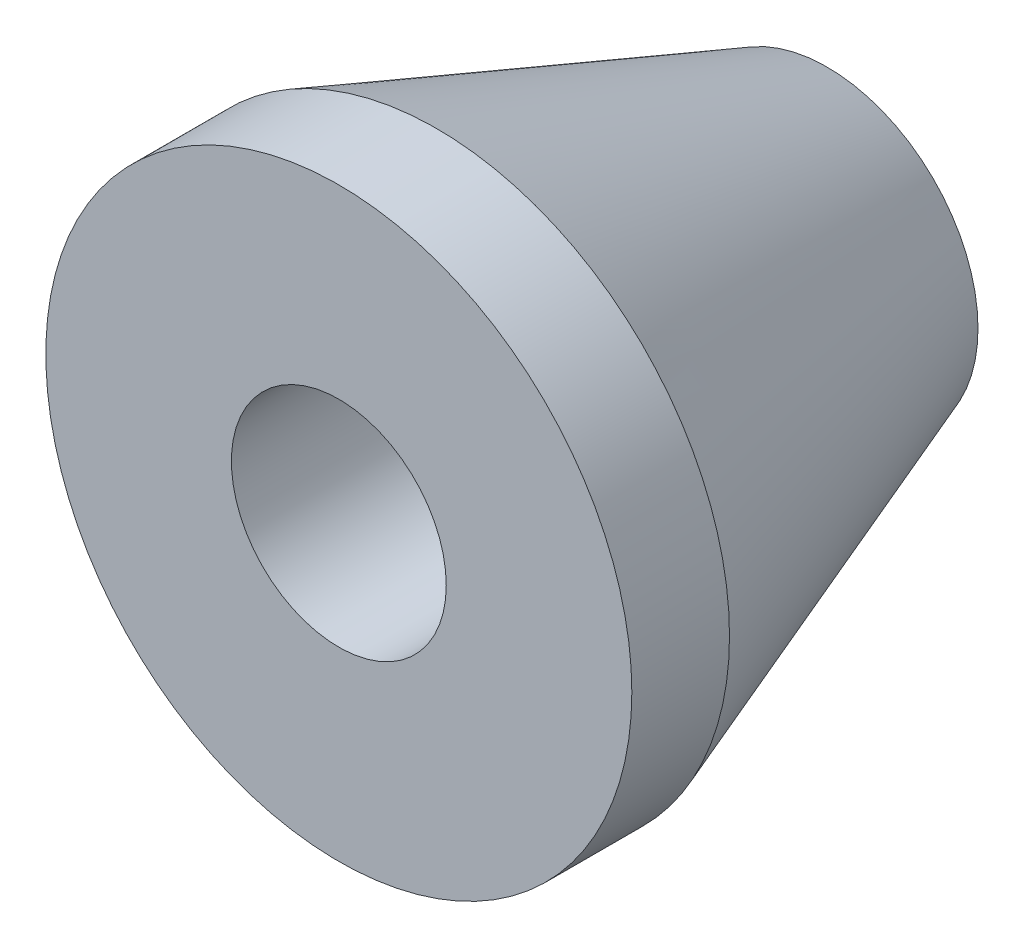
SolidWorks part; units mm, degrees
ref_plane "Front Plane" through (0, 0, 0) normal (0, 0, 1) x (1, 0, 0)
ref_plane "Top Plane" through (0, 0, 0) normal (0, 1, 0) x (1, 0, 0)
ref_plane "Right Plane" through (0, 0, 0) normal (1, 0, 0) x (0, 0, -1)
sketch "Sketch1" plane through (0, 0, 0) normal (1, 0, 0) x (0, 0, -1)
  line L0 (-33.8109, 0) -> (41.1013, 0) construction
  line L1 (0, 11) -> (0, 30)
  line L2 (0, 30) -> (10, 30)
  line L3 (10, 30) -> (50, 15.4412)
  line L4 (50, 15.4412) -> (50, 11)
  line L5 (50, 11) -> (0, 11)
  dimension "D1" = 60
  dimension "D2" = 22
  dimension "D3" = 10
  dimension "D4" = 50
  dimension "D5" = 20
revolve "Revolve1" add sketch "Sketch1" angle 360 about L0
